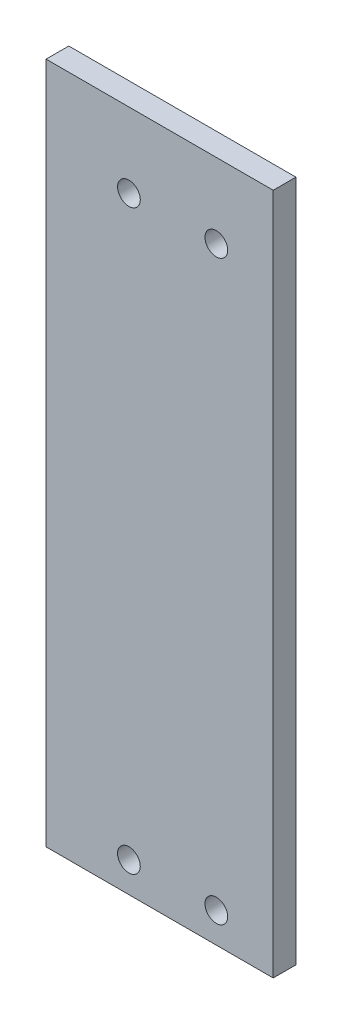
SolidWorks part; units mm, degrees
material "AISI 316 Stainless Steel Sheet (SS)"
ref_plane "Front Plane" through (0, 0, 0) normal (0, 0, 1) x (1, 0, 0)
ref_plane "Top Plane" through (0, 0, 0) normal (0, 1, 0) x (1, 0, 0)
ref_plane "Right Plane" through (0, 0, 0) normal (1, 0, 0) x (0, 0, -1)
sketch "Sketch2" plane through (0, 0, 0) normal (0, 0, 1) x (1, 0, 0)
  line L2 (35.7329, 150.1882) -> (35.7329, 0)
  line L3 (-14.2671, 150.1882) -> (-14.2671, 0)
  line L4 (-14.2671, 150.1882) -> (35.7329, 150.1882)
  line L5 (-14.2671, 0) -> (35.7329, 0)
  line L6 (138.7706, 70.1882) -> (-82.0587, 70.1882) construction
  circle A0 centre (23.211, 6.6473) radius 2.5
  circle A1 centre (3.9684, 6.6473) radius 2.5
  circle A2 centre (3.9684, 133.7291) radius 2.5
  circle A3 centre (23.211, 133.7291) radius 2.5
  point P20 (23.211, 6.6473)
  point P24 (3.9684, 6.6473)
  point P25 (36.0962, 6.6473)
  dimension "D1" = 5
  dimension "D2" = 5
  dimension "D3" = 80
extrude "Boss-Extrude1" add sketch "Sketch2" along normal blind 5
